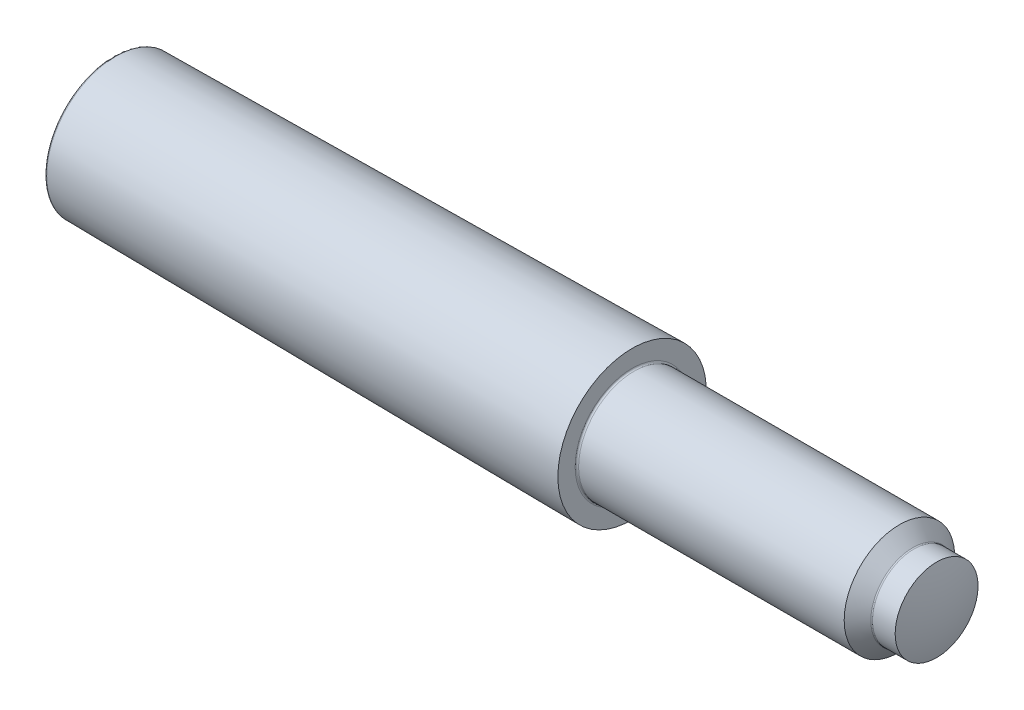
SolidWorks part; units mm, degrees
revolve "Body" add sketch "BodySke" angle 360 about L0
sketch "BodySke" plane through (0, 0, 0) normal (0, 0, 1) x (1, 0, 0)
  line L0 (-8.7403, 0) -> (75.0119, 0) construction
  line L1 (0, 0) -> (0, 10)
  line L2 (0, 10) -> (75, 10.75)
  line L3 (75, 10.75) -> (75, 8)
  line L4 (75, 8) -> (113.7, 8)
  line L5 (113.7, 8) -> (115.7, 6)
  line L6 (115.7, 6) -> (119.0788, 6)
  line L7 (0, 0) -> (120, 0)
  line L8 (81, 20.1179) -> (81, -6.4248) construction
  line L10 (83, 20.1179) -> (83, -6.4248) construction
  arc A0 (120, 0) -> (119.0788, 6) centre (100, 0) ccw
  dimension "Head_rad" = 20
  dimension "Length" = 120
  dimension "Diameter" = 20
  dimension "Thread_dia" = 16
  dimension "Thread_len" = 39
  dimension "Thread_clr" = 6
  dimension "Head_dia" = 12
  dimension "Head_ht" = 4.3
  dimension "D2" = 0.573
  dimension "Advance" = 2
  dimension "D1" = 45
cosmetic thread "ThreadCosmetic" [suppressed] parameters "Length"=34.7, "Thread_minor"=13.797
ref_plane "Front" through (0, 0, 0) normal (0, 0, 1) x (1, 0, 0)
ref_plane "Top" through (0, 0, 0) normal (0, 1, 0) x (1, 0, 0)
ref_plane "Right" through (0, 0, 0) normal (1, 0, 0) x (0, 0, -1)
sketch "ThdSchSke" plane through (0, 0, 0) normal (0, 0, 1) x (1, 0, 0)
  line L0 (81, 6.8985) -> (80.1937, 8.05)
  line L1 (81, 0) -> (81, 10.6732) construction
  line L2 (81, 6.8985) -> (81.8063, 8.05)
  line L3 (81.8063, 8.05) -> (80.1937, 8.05)
  line L4 (112.0749, 0) -> (123.8916, 0) construction
  line L8 (75, -10.75) -> (75, 10.75) construction
  dimension "Thread_minor" = 13.797
  dimension "D1" = 70
  dimension "Inset" = 6
revolve "ThreadSchematic" [suppressed] cut sketch "ThdSchSke" angle 360 about L4
pattern_linear "ThdSchPat" [suppressed]
fillet "Fillets" radius 0.25 3 edges at (0, 0, 10) (75, 0, 8) (115.7, 0, 6)
equation "' \"Diameter@BodySke\" = 20"
equation "' \"Thread_dia@BodySke\" = 16"
equation "' \"Advance@BodySke\" = 2"
equation "' \"Thread_clr@BodySke\" = 6"
equation "' \"Thread_len@BodySke\" = 39"
equation "' \"Head_dia@BodySke\" = 12"
equation "' \"Head_ht@BodySke\" = 4.3"
equation "' \"Length@BodySke\" = 120"
equation "' \"Thread_minor@ThreadCosmetic\"  = 13.797"
equation "' \"Thread_minor@ThreadCosmetic\" = 13.797"
equation "' \"Diameter@BodySke\" = 5"
equation "' \"Thread_dia@BodySke\" = 5"
equation "' \"Advance@BodySke\" = 0.8"
equation "' \"Thread_clr@BodySke\" = 2.4"
equation "' \"Thread_len@BodySke\" = 15.6"
equation "' \"Head_dia@BodySke\" = 3.5"
equation "' \"Head_ht@BodySke\" = 1.5"
equation "' \"Length@BodySke\" = 40"
equation "' \"Thread_minor@ThreadCosmetic\"  = 4.11"
equation "' \"Thread_minor@ThreadCosmetic\" = 4.11"
equation "\"Head_rad@BodySke\" = \"Diameter@BodySke\""
equation "\"Length@ThreadCosmetic\" = \"Thread_len@BodySke\" - \"Head_ht@BodySke\""
equation "\"Thread_minor@ThdSchSke\" = \"Thread_minor@ThreadCosmetic\" "
equation "\"DieOD@ThdSchSke\" =  \"Thread_dia@BodySke\" + 0.1"
equation "\"Inset@ThdSchSke\" = \"Thread_clr@BodySke\""
equation "\"Num_threads@ThdSchPat\" = int(  ( \"Thread_len@BodySke\" - \"Head_ht@BodySke\" -   (\"Thread_minor@ThdSchSke\" - \"Head_dia@BodySke\" ) / 2 * tan(45 * 0.0174533) ) / \"Advance@BodySke\" + 0.999 )"
equation "\"Advance@ThdSchPat\" = (  \"Thread_len@BodySke\"  - \"Head_ht@BodySke\"  - (\"Thread_minor@ThdSchSke\" - \"Head_dia@BodySke\" ) / 2 * tan(45 * 0.0174533)) /  (\"Num_threads@ThdSchPat\" ) 'relax it"
